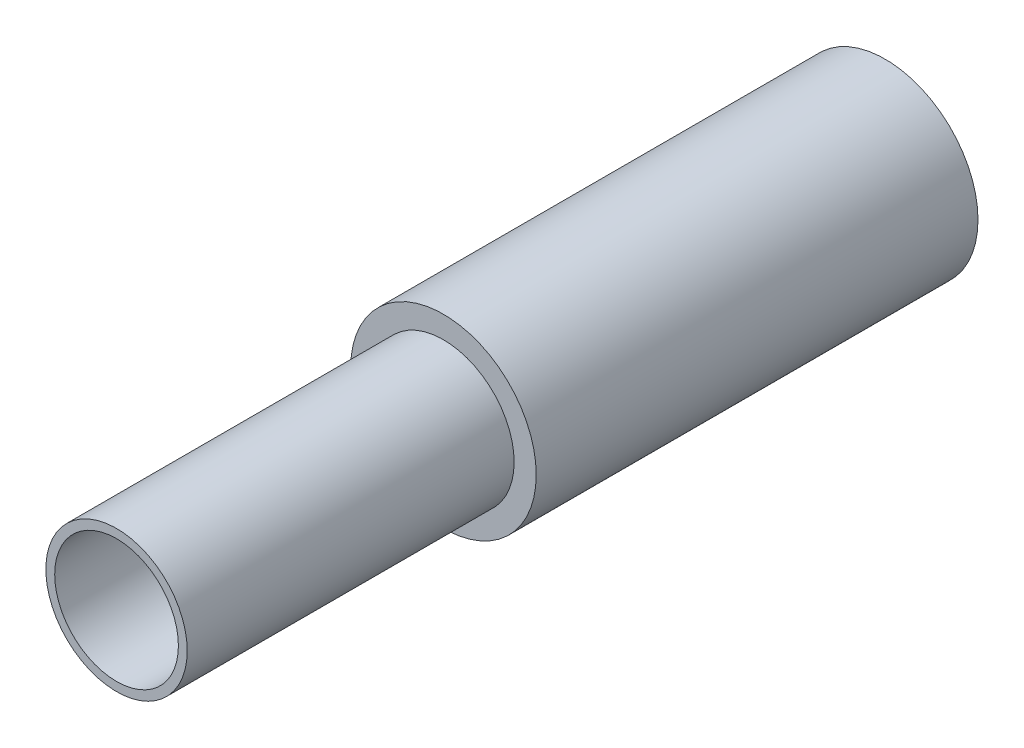
SolidWorks part; units mm, degrees
ref_plane "Front Plane" through (0, 0, 0) normal (0, 0, 1) x (1, 0, 0)
ref_plane "Top Plane" through (0, 0, 0) normal (0, 1, 0) x (1, 0, 0)
ref_plane "Right Plane" through (0, 0, 0) normal (1, 0, 0) x (0, 0, -1)
sketch "Sketch1" plane through (0, 0, 0) normal (0, 0, 1) x (1, 0, 0)
  circle A0 centre (0, 0) radius 8
  dimension "D1" = 16
extrude "Boss-Extrude2" add sketch "Sketch1" along normal blind 37
sketch "Sketch4" plane through (0, 0, 0) normal (0, 0, -1) x (-1, 0, 0)
  circle A0 centre (0, 0) radius 10.5
  dimension "D1" = 21
extrude "Boss-Extrude4" add sketch "Sketch4" along normal blind 50
shell "Shell1" thickness 1
sketch "Sketch5" plane through (0, 0, -50) normal (0, 0, -1) x (-1, 0, 0)
  circle A0 centre (0, 0) radius 9.5
  dimension "D1" = 19
extrude "Cut-Extrude2" cut sketch "Sketch5" against normal up to next
